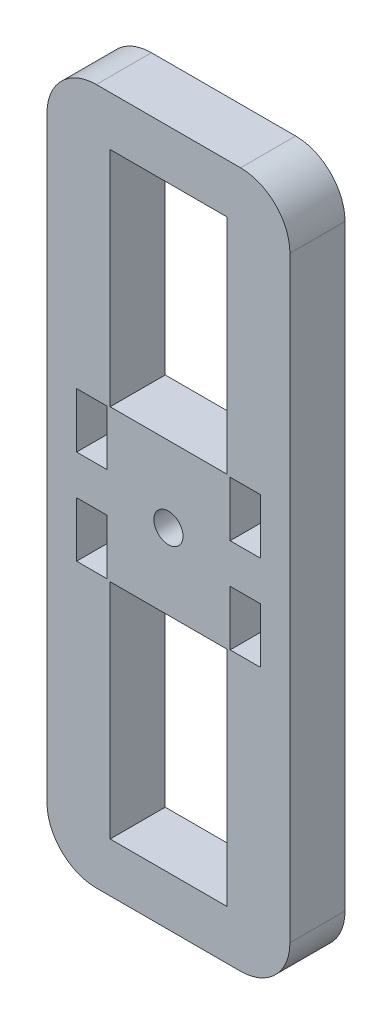
SolidWorks part; units mm, degrees
material "Acrylic (Medium-high impact)"
ref_plane "Front Plane" through (0, 0, 0) normal (0, 0, 1) x (1, 0, 0)
ref_plane "Top Plane" through (0, 0, 0) normal (0, 1, 0) x (1, 0, 0)
ref_plane "Right Plane" through (0, 0, 0) normal (1, 0, 0) x (0, 0, -1)
sketch "Sketch1" plane through (0, 0, 0) normal (0, 0, 1) x (1, 0, 0)
  line L0 (709.7907, 498.1997) -> (721.6007, 498.1997)
  line L1 (721.6007, 498.1997) -> (721.6007, 475.6297)
  line L2 (721.6007, 475.6297) -> (709.7907, 475.6297)
  line L3 (709.7907, 475.6297) -> (709.7907, 498.1997)
  line L4 (715.6957, 432.7097) -> (723.0007, 432.7097)
  line L5 (715.6957, 503.1997) -> (708.3907, 503.1997)
  line L6 (715.6957, 503.1997) -> (723.0007, 503.1997)
  line L7 (715.6957, 460.2797) -> (715.6957, 475.6297) construction
  line L8 (709.7907, 498.1997) -> (703.3907, 498.1997) construction
  line L9 (721.6007, 498.1997) -> (728.0007, 498.1997) construction
  line L10 (709.4457, 475.5297) -> (706.3907, 475.5297)
  line L11 (728.0007, 498.1997) -> (728.0007, 437.7097)
  line L12 (709.4457, 475.5297) -> (709.4457, 469.9547)
  line L13 (706.3907, 469.9547) -> (709.4457, 469.9547)
  line L14 (706.3907, 469.9547) -> (706.3907, 475.5297)
  line L15 (703.3907, 498.1997) -> (703.3907, 437.7097)
  line L16 (721.9457, 475.5297) -> (725.0007, 475.5297)
  line L17 (725.0007, 469.9547) -> (725.0007, 475.5297)
  line L18 (706.3907, 465.9547) -> (709.4457, 465.9547)
  line L19 (721.9457, 475.5297) -> (721.9457, 469.9547)
  line L20 (721.9457, 460.3797) -> (725.0007, 460.3797)
  line L21 (725.0007, 465.9547) -> (725.0007, 460.3797)
  line L22 (715.6957, 432.7097) -> (708.3907, 432.7097)
  line L23 (725.1007, 469.4297) -> (49717.0384, 469.4297) construction
  line L24 (709.6907, 466.4797) -> (715.6957, 466.4797) construction
  line L25 (725.1007, 466.4797) -> (49717.0384, 466.4797) construction
  line L26 (709.4457, 460.3797) -> (706.3907, 460.3797)
  line L27 (706.3907, 465.9547) -> (706.3907, 460.3797)
  line L28 (725.0007, 465.9547) -> (721.9457, 465.9547)
  line L29 (721.9457, 460.3797) -> (721.9457, 465.9547)
  line L30 (-282.9616, 469.4297) -> (706.3907, 469.4297) construction
  line L31 (-282.9616, 466.4797) -> (703.3907, 466.4797) construction
  line L32 (725.0007, 469.9547) -> (721.9457, 469.9547)
  line L33 (709.4457, 460.3797) -> (709.4457, 465.9547)
  line L37 (709.7907, 460.2797) -> (709.7907, 437.7097)
  line L38 (721.6007, 460.2797) -> (709.7907, 460.2797)
  line L39 (721.6007, 437.7097) -> (721.6007, 460.2797)
  line L40 (709.7907, 437.7097) -> (721.6007, 437.7097)
  line L171 (-296.3722, 467.9547) -> (49703.6278, 467.9547) construction
  circle A0 centre (715.6957, 467.9547) radius 1.475
  arc A1 (708.3907, 432.7097) -> (703.3907, 437.7097) centre (708.3907, 437.7097) cw
  arc A2 (708.3907, 503.1997) -> (703.3907, 498.1997) centre (708.3907, 498.1997) ccw
  arc A3 (723.0007, 503.1997) -> (728.0007, 498.1997) centre (723.0007, 498.1997) cw
  arc A4 (723.0007, 432.7097) -> (728.0007, 437.7097) centre (723.0007, 437.7097) ccw
  point P6 (715.6957, 504.6992)
  point P33 (715.6957, 475.6297)
  point P37 (715.6957, 467.9547)
  point P46 (715.6957, 431.2102)
  dimension "D1" = 6.1
  dimension "D4" = 2.95
  dimension "D2" = 4
  dimension "D3" = 0.1
  dimension "D5" = 22.57
  dimension "D6" = 11.81
  dimension "D7" = 3
  dimension "D8" = 5
  dimension "D9" = 12.5
  dimension "D10" = 11.81
extrude "Boss-Extrude1" add sketch "Sketch1" along normal blind 5.58
